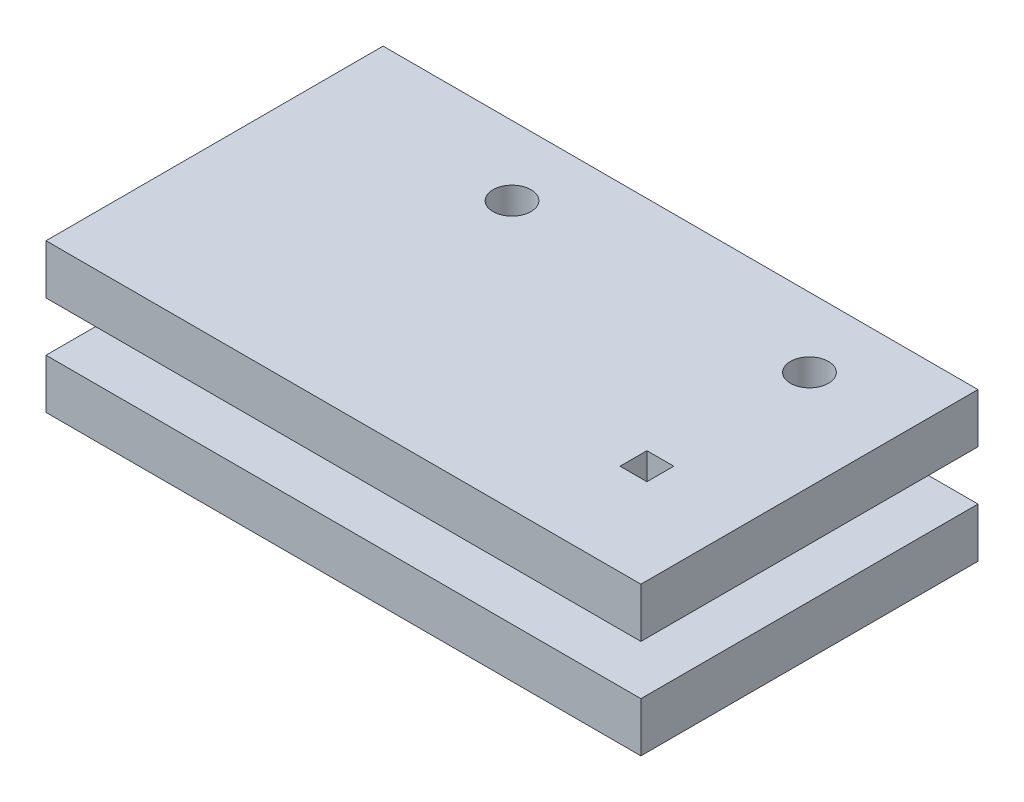
SolidWorks part; units mm, degrees
ref_plane "Front Plane" through (0, 0, 0) normal (0, 0, 1) x (1, 0, 0)
ref_plane "Top Plane" through (0, 0, 0) normal (0, 1, 0) x (1, 0, 0)
ref_plane "Right Plane" through (0, 0, 0) normal (1, 0, 0) x (0, 0, -1)
sketch "Sketch1" plane through (0, 0, 0) normal (0, 0, 1) x (1, 0, 0)
  line L1 (-38.1, 9.525) -> (38.1, 9.525)
  line L2 (-38.1, 9.525) -> (-38.1, -9.525)
  line L3 (-38.1, -9.525) -> (38.1, -9.525)
  line L4 (38.1, 9.525) -> (38.1, -9.525)
  line L5 (-38.1, 9.525) -> (38.1, -9.525) construction
  line L6 (-38.1, -9.525) -> (38.1, 9.525) construction
  point P0 (0, 0)
  dimension "D1" = 76.2
  dimension "D2" = 19.05
extrude "Boss-Extrude1" add sketch "Sketch1" along normal blind 43.18
sketch "Sketch2" plane through (0, 0, 0) normal (0, 0, -1) x (-1, 0, 0)
  line L0 (38.1, 9.525) -> (38.1, -9.525) construction
  line L1 (-38.1, -3.175) -> (38.1, -3.175)
  line L2 (-38.1, -3.175) -> (-38.1, 3.175)
  line L3 (-38.1, 3.175) -> (38.1, 3.175)
  line L4 (38.1, -3.175) -> (38.1, 3.175)
  line L5 (-38.1, -3.175) -> (38.1, 3.175) construction
  line L6 (-38.1, 3.175) -> (38.1, -3.175) construction
  point P0 (0, 0)
  dimension "D1" = 6.35
extrude "Cut-Extrude1" cut sketch "Sketch2" against normal through all
sketch "Sketch3" plane through (0, -9.525, 0) normal (0, -1, 0) x (1, 0, 0)
  line L0 (0, 43.18) -> (0, 8.89) construction
  line L1 (-38.1, 43.18) -> (38.1, 43.18) construction
  line L2 (38.1, 8.89) -> (25.4, 8.89) construction
  line L3 (38.1, 43.18) -> (38.1, 0) construction
  line L4 (-38.1, 8.89) -> (-12.7, 8.89) construction
  line L5 (-38.1, 43.18) -> (-38.1, 0) construction
  line L6 (25.4, 8.89) -> (25.4, 42.9695) construction
  line L7 (23.6783, 27.986) -> (27.1217, 27.986)
  line L8 (23.6783, 27.986) -> (23.6783, 31.4295)
  line L9 (23.6783, 31.4295) -> (27.1217, 31.4295)
  line L10 (27.1217, 27.986) -> (27.1217, 31.4295)
  line L11 (23.6783, 27.986) -> (27.1217, 31.4295) construction
  line L12 (23.6783, 31.4295) -> (27.1217, 27.986) construction
  line L13 (-38.1, 0) -> (38.1, 0) construction
  circle A0 centre (25.4, 8.89) radius 2.4349
  circle A1 centre (-12.7, 8.89) radius 2.4349
  point P17 (25.4, 29.7077)
  dimension "D3" = 4.8698
  dimension "D1" = 8.89
  dimension "D2" = 12.7
  dimension "D4" = 25.4
  dimension "D6" = 4.8698
extrude "Cut-Extrude2" cut sketch "Sketch3" against normal through all both and the other way through all
